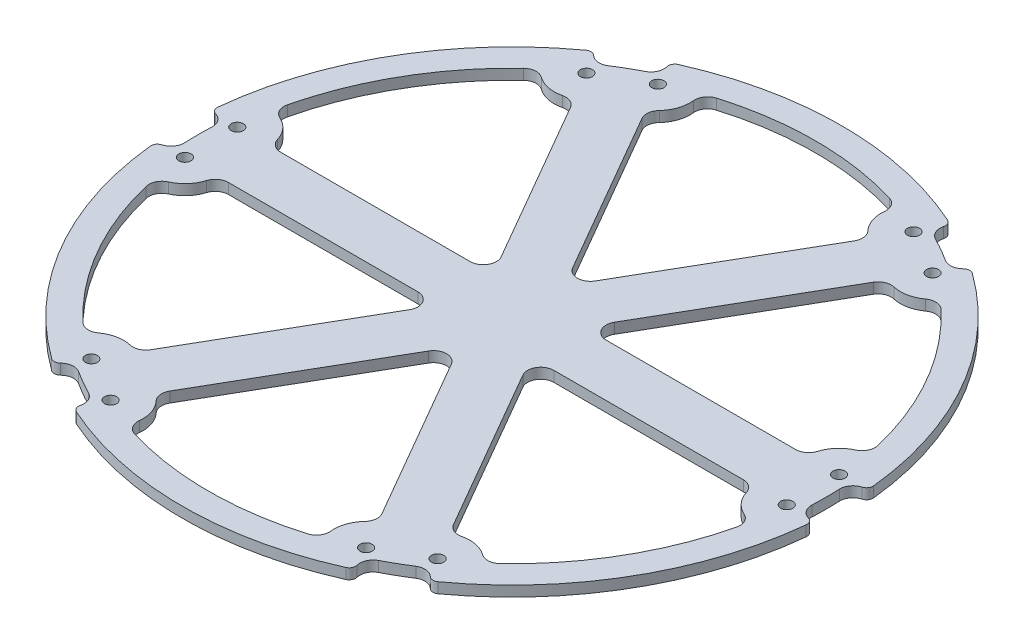
SolidWorks part; units mm, degrees
ref_plane "Front Plane" through (0, 0, 0) normal (0, 0, 1) x (1, 0, 0)
ref_plane "Top Plane" through (0, 0, 0) normal (0, 1, 0) x (1, 0, 0)
ref_plane "Right Plane" through (0, 0, 0) normal (1, 0, 0) x (0, 0, -1)
sketch "Sketch1" plane through (0, 0, 0) normal (0, 1, 0) x (1, 0, 0)
  circle A0 centre (0, 0) radius 76.2
  dimension "D1" = 152.4
extrude "Boss-Extrude1" add sketch "Sketch1" along normal blind 2.54
sketch "Sketch2" plane through (0, 2.54, 0) normal (0, 1, 0) x (1, 0, 0)
  line L0 (-32.4682, 68.9366) -> (-34.0916, 72.3834)
  line L1 (32.4682, 68.9366) -> (34.0916, 72.3834)
  line L2 (-32.4682, 68.9366) -> (-84.6995, 44.3363) construction
  line L3 (32.4682, 68.9366) -> (48.6929, 61.295) construction
  line L4 (0, -1.397) -> (0, 1.397) construction
  line L5 (0, 103.2188) -> (0, 0) construction
  line L6 (0, 0) -> (-56.1327, 97.2247) construction
  line L7 (-32.4682, 68.9366) -> (-43.4667, 62.5866) construction
  circle A0 centre (0, 0) radius 76.2 construction
  arc A1 (32.4682, 68.9366) -> (-32.4682, 68.9366) centre (0, 0) ccw
  arc A2 (-34.0916, 72.3834) -> (34.0916, 72.3834) centre (0, 0) cw
  point P11 (0, 80.01)
  point P15 (-37.9675, 65.7616)
  point P16 (0, 0)
  dimension "D1" = 80.01
  dimension "D2" = 30
  dimension "D3" = 12.7
extrude "cutoutFiller" add sketch "Sketch2" against normal up to surface (2.54 mm away) up to face at (0, 0, 76.2)
fillet "quarterEndmillFillet" radius 3.175 2 edges at (32.4682, 1.27, -68.9366) (-32.4682, 1.27, -68.9366)
fillet "handlingFillet" radius 1.5875 2 edges at (-34.0916, 1.27, -72.3834) (34.0916, 1.27, -72.3834)
sketch "Sketch4" plane through (0, 0, 0) normal (0, -1, 0) x (1, 0, 0)
  line L0 (0, -80.01) -> (0, 0) construction
  line L1 (0, 0) -> (-38.1, -65.9911) construction
  line L2 (-6.35, -73.3858) -> (-6.35, -23.6985) construction
  line L3 (-6.35, -23.6985) -> (-29.6152, -63.995)
  line L4 (-6.35, -23.6985) -> (0, -12.7)
  line L5 (6.35, -23.6985) -> (29.6152, -63.995)
  line L6 (6.35, -23.6985) -> (0, -12.7)
  arc A3 (-33.5895, -71.1821) -> (-32.6999, -73.0227) centre (-32.0511, -71.5738) ccw construction
  arc A4 (-33.5895, -71.1821) -> (-35.1997, -67.5827) centre (-36.6663, -70.3986) ccw construction
  arc A5 (35.1997, -67.5827) -> (-35.1997, -67.5827) centre (0, 0) ccw construction
  arc A6 (-32.6999, -73.0227) -> (32.6999, -73.0227) centre (0, 0) ccw construction
  arc A7 (-32.6999, -73.0227) -> (0, -80.01) centre (0, 0) ccw construction
  arc A8 (-29.6152, -63.995) -> (-29.6152, -63.995) centre (-29.6152, -63.995) ccw
  arc A9 (-33.5895, -71.1821) -> (-32.6999, -73.0227) centre (-32.0511, -71.5738) ccw construction
  arc A10 (-33.5895, -71.1821) -> (-35.1997, -67.5827) centre (-36.6663, -70.3986) ccw construction
  arc A11 (-38.1, -65.9911) -> (-35.1997, -67.5827) centre (0, 0) ccw construction
  arc A12 (-27.3551, -68.3922) -> (-29.6152, -63.995) centre (-36.6663, -70.3986) ccw
  arc A13 (-27.3551, -68.3922) -> (-27.3551, -68.3922) centre (-27.3551, -68.3922) ccw
  arc A14 (-27.3551, -68.3922) -> (-6.35, -73.3858) centre (0, 0) ccw
  arc A15 (-6.35, -73.3858) -> (6.35, -73.3858) centre (0, 0) ccw
  arc A16 (27.3551, -68.3922) -> (6.35, -73.3858) centre (0, 0) cw
  arc A17 (27.3551, -68.3922) -> (29.6152, -63.995) centre (36.6663, -70.3986) cw
  point P12 (0, -80.01)
  dimension "D1" = 30
  dimension "D2" = 6.35
extrude "Cut-Extrude1" cut sketch "Sketch4" against normal through all both and the other way through all
fillet "Fillet7" radius 3.175 5 edges at (0, 1.27, -12.7) (27.3551, 1.27, -68.3922) (-27.3551, 1.27, -68.3922)
pattern_circular "CirPattern5" count 6 over 360 about axis through (0, 0, 0) along (0, 1, 0) of "cutoutFiller", "quarterEndmillFillet", "handlingFillet", "Cut-Extrude1", "Fillet7"
hole_wizard "#4 Clearance Hole1" positions "Sketch5" profile "Sketch6" hole size "#4" standard "ANSI Inch" end condition through all
sketch "Sketch5" plane through (0, 0, 0) normal (0, -1, 0) x (-1, 0, 0)
  line L2 (73.025, 6.35) -> (73.025, -6.35) construction
  arc A2 (76.1282, -3.3075) -> (76.1282, 3.3075) centre (0, 0) ccw construction
  point P0 (73.025, 6.35)
  point P2 (73.025, -6.35)
  point P30 (73.025, 0)
  point P34 (76.2, 0)
  dimension "D1" = 3.175
  dimension "D2" = 12.7
sketch "Sketch6" plane through (-73.025, 0, -6.35) normal (1, 0, 0) x (0, 0, -1)
  line L0 (0, 0) -> (0, 2.54)
  line L1 (0, 2.54) -> (1.4732, 2.54)
  line L2 (1.4732, 2.54) -> (1.4732, 0)
  line L5 (1.4732, 0) -> (0, 0)
  line L11 (0, -6.35) -> (0, 107.95) construction
  dimension "Thru Hole Dia." = 2.9464
  dimension "Thru Hole Depth" = 2.54
sketch "Sketch7" plane through (0, 2.54, 0) normal (0, 1, 0) x (1, 0, 0)
  line L0 (-73.025, 14.1732) -> (-73.025, 7.8232)
  line L1 (-73.025, 4.8768) -> (-73.025, -4.8768)
  line L2 (-73.025, -7.8232) -> (-73.025, -14.1732)
  circle A0 centre (-73.025, -6.35) radius 1.4732 construction
  circle A1 centre (-73.025, 6.35) radius 1.4732 construction
  arc A4 (-73.025, 4.8768) -> (-73.025, 7.8232) centre (-73.025, 6.35) ccw
  arc A5 (-73.025, -7.8232) -> (-73.025, -4.8768) centre (-73.025, -6.35) ccw
  arc A6 (-68.4555, 0) -> (-73.025, 14.1732) centre (-73.025, 6.35) ccw
  arc A7 (-73.025, -14.1732) -> (-68.4555, 0) centre (-73.025, -6.35) ccw
  circle A8 centre (-73.025, 6.35) radius 7.8232 construction
  circle A9 centre (-73.025, -6.35) radius 7.8232 construction
  circle A10 centre (-73.025, -6.35) radius 1.4732 construction
  circle A11 centre (-73.025, 6.35) radius 1.4732 construction
  point P14 (0, 0)
  dimension "D1" = 6.35
extrude "Boss-Extrude3" add sketch "Sketch7" against normal up to surface (2.54 mm away) up to face at (-73.025, 0, -7.8232)
pattern_circular "CirPattern6" count 6 over 360 about axis through (0, 0, 0) along (0, 1, 0) of "#4 Clearance Hole1", "Boss-Extrude3"
fillet "Fillet8" radius 3.175 24 edges at (-72.2904, 1.27, -14.1386) (-65.2018, 1.27, -6.35) (-65.2018, 1.27, 6.35) (-72.2904, 1.27, 14.1386) (-48.3896, 1.27, 55.536) (-38.1002, 1.27, 53.2914) (-27.1016, 1.27, 59.6414) (-23.9008, 1.27, 69.6746) (23.9008, 1.27, 69.6746) (27.1016, 1.27, 59.6414) (38.1002, 1.27, 53.2914) (48.3896, 1.27, 55.536) (72.2904, 1.27, 14.1386) (65.2018, 1.27, 6.35) (65.2018, 1.27, -6.35) (72.2904, 1.27, -14.1386) (48.3896, 1.27, -55.536) (38.1002, 1.27, -53.2914) (27.1016, 1.27, -59.6414) (23.9008, 1.27, -69.6746) (-23.9008, 1.27, -69.6746) (-27.1016, 1.27, -59.6414) (-38.1002, 1.27, -53.2914) (-48.3896, 1.27, -55.536)
